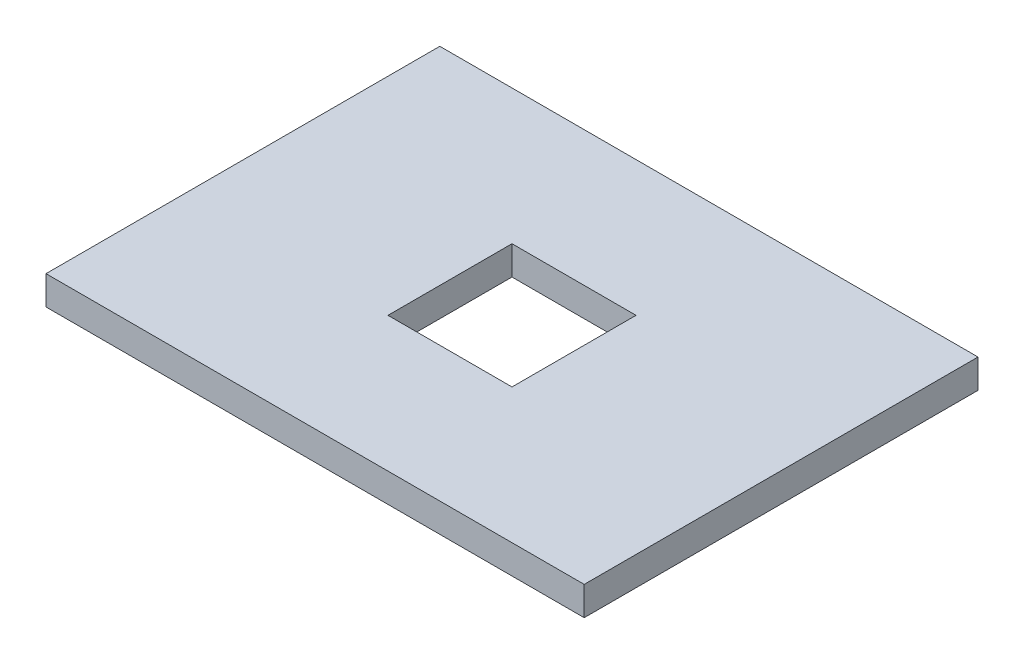
SolidWorks part; units mm, degrees
ref_plane "Front Plane" through (0, 0, 0) normal (0, 0, 1) x (1, 0, 0)
ref_plane "Top Plane" through (0, 0, 0) normal (0, 1, 0) x (1, 0, 0)
ref_plane "Right Plane" through (0, 0, 0) normal (1, 0, 0) x (0, 0, -1)
sketch "Sketch1" plane through (0, 0, 0) normal (0, 1, 0) x (1, 0, 0)
  line L1 (-130.175, -95.25) -> (130.175, -95.25)
  line L2 (-130.175, -95.25) -> (-130.175, 95.25)
  line L3 (-130.175, 95.25) -> (130.175, 95.25)
  line L4 (130.175, -95.25) -> (130.175, 95.25)
  line L5 (-130.175, -95.25) -> (130.175, 95.25) construction
  line L6 (-130.175, 95.25) -> (130.175, -95.25) construction
  point P0 (0, 0)
  dimension "D1" = 190.5
  dimension "D2" = 260.35
extrude "Boss-Extrude1" add sketch "Sketch1" along normal blind 13.97
sketch "Sketch3" plane through (0, 13.97, 0) normal (0, 1, 0) x (1, 0, 0)
  line L1 (-30, -30) -> (30, -30)
  line L2 (-30, -30) -> (-30, 30)
  line L3 (-30, 30) -> (30, 30)
  line L4 (30, -30) -> (30, 30)
  line L5 (-30, -30) -> (30, 30) construction
  line L6 (-30, 30) -> (30, -30) construction
  point P0 (0, 0)
  dimension "D1" = 60
extrude "Cut-Extrude2" cut sketch "Sketch3" against normal through all
